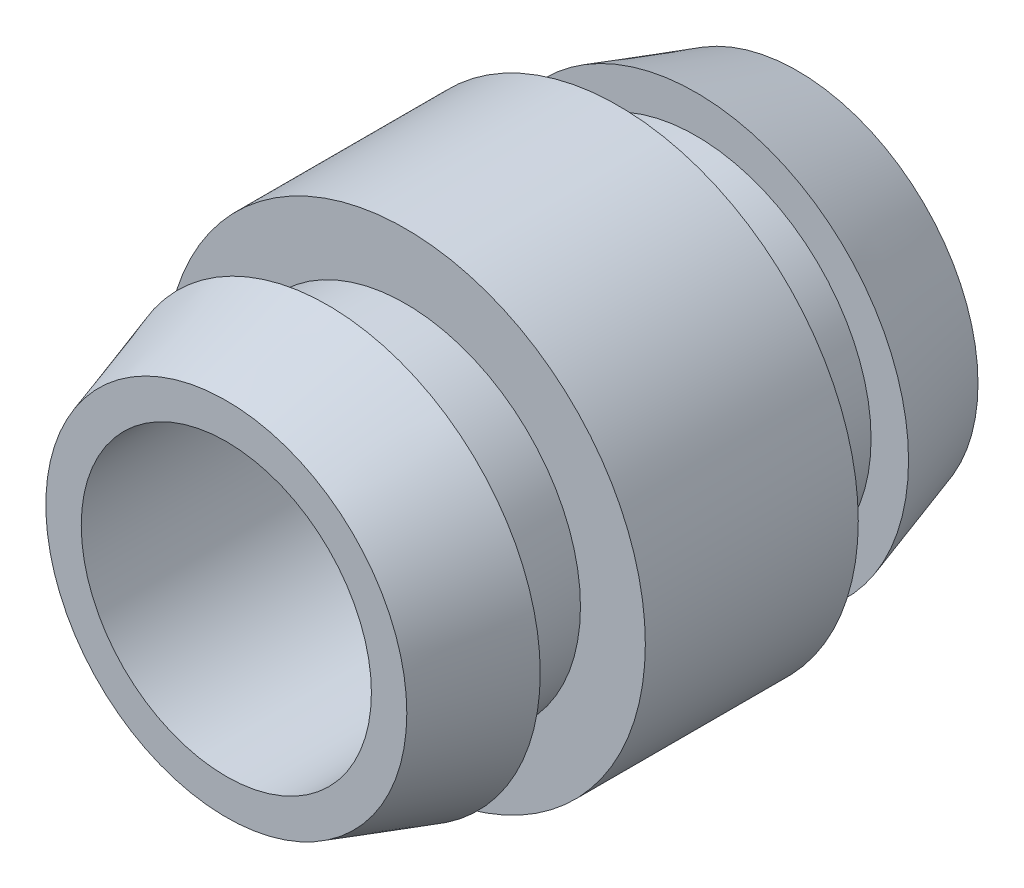
SolidWorks part; units mm, degrees
ref_plane "Front Plane" through (0, 0, 0) normal (0, 0, 1) x (1, 0, 0)
ref_plane "Top Plane" through (0, 0, 0) normal (0, 1, 0) x (1, 0, 0)
ref_plane "Right Plane" through (0, 0, 0) normal (1, 0, 0) x (0, 0, -1)
sketch "Sketch1" plane through (0, 0, 0) normal (1, 0, 0) x (0, 0, -1)
  line L0 (0, 0) -> (36.3308, 0) construction
  line L1 (0, -8.0645) -> (28.448, -8.0645)
  line L2 (28.448, -8.0645) -> (28.448, 0)
  line L3 (28.448, 0) -> (31.75, 0)
  line L4 (31.75, 0) -> (31.75, -10.033)
  line L5 (31.75, -10.033) -> (26.1112, -11.811)
  line L6 (26.1112, -11.811) -> (26.1112, -9.7282)
  line L7 (26.1112, -9.7282) -> (21.7932, -9.7282)
  line L8 (21.7932, -9.7282) -> (21.7932, -13.335)
  line L9 (21.7932, -13.335) -> (9.9568, -13.335)
  line L10 (9.9568, -13.335) -> (9.9568, -9.7282)
  line L11 (9.9568, -9.7282) -> (5.6388, -9.7282)
  line L12 (5.6388, -9.7282) -> (5.6388, -11.811)
  line L13 (5.6388, -11.811) -> (0, -10.033)
  line L14 (0, -10.033) -> (0, -8.0645)
  dimension "D1" = 31.75
  dimension "D2" = 28.448
  dimension "D3" = 28.448
  dimension "D4" = 11.8364
  dimension "D5" = 4.318
  dimension "D6" = 13.335
  dimension "D7" = 8.0645
  dimension "D8" = 9.7282
  dimension "D9" = 10.033
  dimension "D10" = 10.033
  dimension "D11" = 11.811
  dimension "D12" = 11.811
revolve "Revolve1" add sketch "Sketch1" angle 360 about L0
scale "Scale1" scale about centroid uniform scaling yes scale factor 0.6
